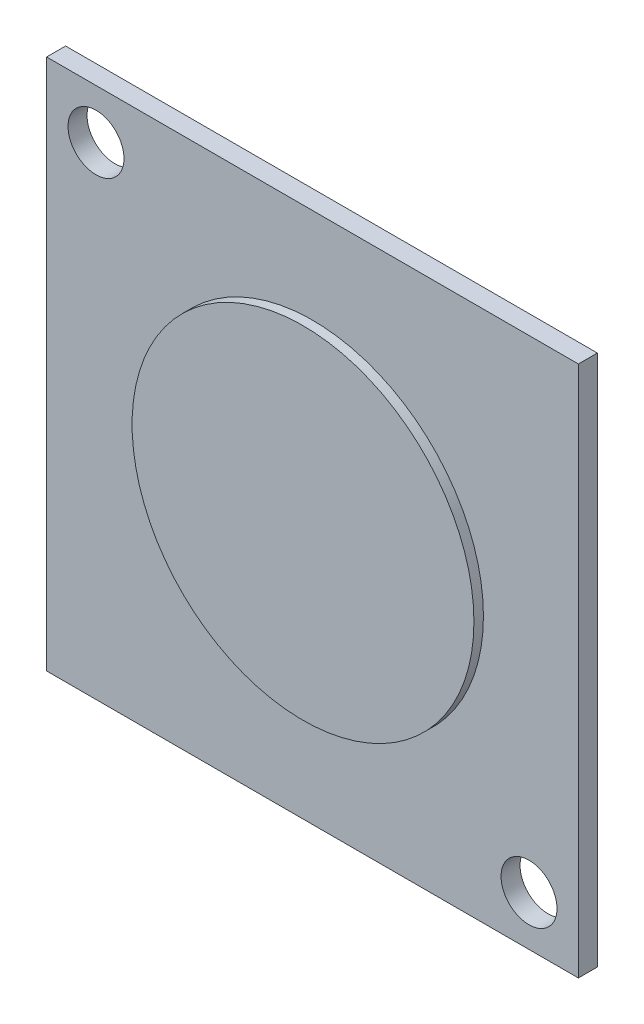
SolidWorks part; units mm, degrees
ref_plane "Front" through (0, 0, 0) normal (0, 0, 1) x (1, 0, 0)
ref_plane "Top" through (0, 0, 0) normal (0, 1, 0) x (1, 0, 0)
ref_plane "Right" through (0, 0, 0) normal (1, 0, 0) x (0, 0, -1)
sketch "Sketch1" plane through (0, 0, 0) normal (0, 0, 1) x (1, 0, 0)
  line L1 (-14, -14) -> (14, -14)
  line L2 (-14, -14) -> (-14, 14)
  line L3 (-14, 14) -> (14, 14)
  line L4 (14, -14) -> (14, 14)
  line L5 (-14, -14) -> (14, 14) construction
  line L6 (-14, 14) -> (14, -14) construction
  point P0 (0, 0)
  dimension "D1" = 28
extrude "Boss-Extrude1" add sketch "Sketch1" along normal blind 1
sketch "Sketch2" plane through (0, 0, 1) normal (0, 0, 1) x (1, 0, 0)
  circle A0 centre (0, 0) radius 9
  dimension "D1" = 18
extrude "Boss-Extrude2" add sketch "Sketch2" along normal blind 0.5
hole_wizard "#4 Clearance Hole1" positions "Sketch3" profile "Sketch4" hole size "#4" standard "ANSI Inch" end condition through all
sketch "Sketch3" plane through (0, 0, 1) normal (0, 0, 1) x (1, 0, 0)
  line L0 (0, 14) -> (0, -14) construction
  line L1 (14, 14) -> (-14, 14) construction
  line L2 (-14, -14) -> (14, -14) construction
  line L5 (-11.4, -11.4) -> (11.4, -11.4) construction
  line L6 (-11.4, -11.4) -> (-11.4, 11.4) construction
  line L7 (-11.4, 11.4) -> (11.4, 11.4) construction
  line L8 (11.4, -11.4) -> (11.4, 11.4) construction
  line L9 (-11.4, -11.4) -> (11.4, 11.4) construction
  line L10 (-11.4, 11.4) -> (11.4, -11.4) construction
  point P209 (-11.4, 11.4)
  point P210 (11.4, -11.4)
  point P213 (0, 0)
  dimension "D1" = 11.4
sketch "Sketch4" plane through (11.4, -11.4, 1) normal (1, 0, 0) x (0, -1, 0)
  line L0 (0, 0) -> (0, 1)
  line L1 (0, 1) -> (1.4732, 1)
  line L2 (1.4732, 1) -> (1.4732, 0)
  line L5 (1.4732, 0) -> (0, 0)
  line L11 (0, -6.35) -> (0, 107.95) construction
  dimension "Thru Hole Dia." = 2.9464
  dimension "Thru Hole Depth" = 1
